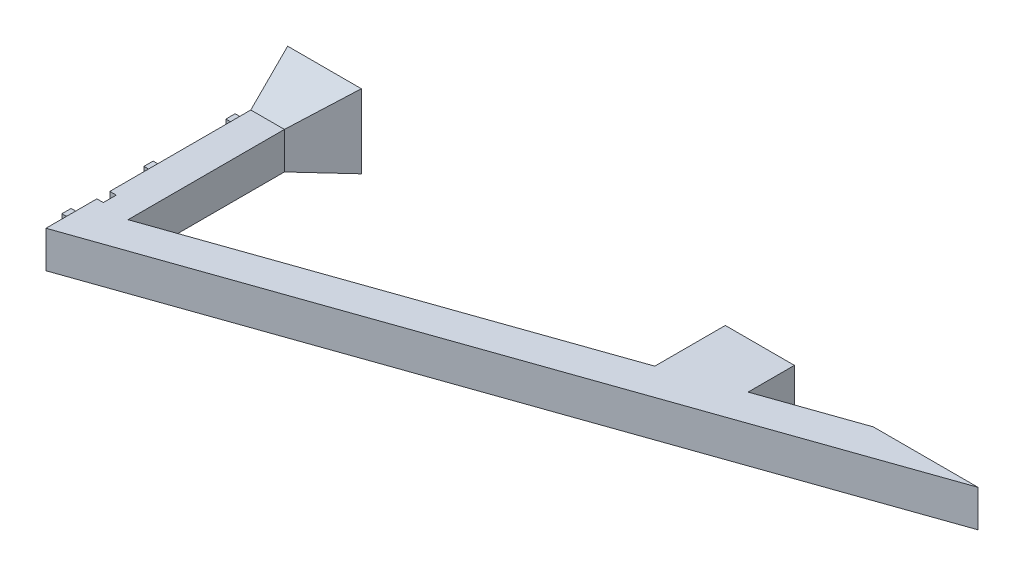
SolidWorks part; units mm, degrees
ref_plane "Přední rovina" through (0, 0, 0) normal (0, 0, 1) x (1, 0, 0)
ref_plane "Horní rovina" through (0, 0, 0) normal (0, 1, 0) x (1, 0, 0)
ref_plane "Pravá rovina" through (0, 0, 0) normal (1, 0, 0) x (0, 0, -1)
sketch "Skica1" plane through (0, 0, 0) normal (0, 1, 0) x (1, 0, 0)
  line L0 (0, 0) -> (0, -55.45)
  line L1 (0, -55.45) -> (149.85, -3)
  line L2 (149.85, -3) -> (127.1478, -3)
  line L3 (127.1478, -3) -> (107, -10.0521)
  line L4 (107, -10.0521) -> (107, 0)
  line L5 (107, 0) -> (92, 0)
  line L6 (92, 0) -> (92, -15.3023)
  line L7 (92, -15.3023) -> (7.3, -44.9487)
  line L8 (7.3, -44.9487) -> (7.3, 0)
  line L9 (7.3, 0) -> (0, 0)
  point P3 (92, -7.6512)
  dimension "D1" = 55.45
  dimension "D2" = 7.3
  dimension "D3" = 15
  dimension "D4" = 3
  dimension "D5" = 7.5
  dimension "D6" = 7.5
  dimension "D7" = 84.7
  dimension "D8" = 149.85
extrude "Přidat vysunutím1" add sketch "Skica1" along normal blind 8
sketch "Skica2" plane through (0, 8, 0) normal (0, 1, 0) x (1, 0, 0)
  line L0 (0, 0) -> (0, -55.45) construction
  line L1 (0, -41.6) -> (1.4, -41.6)
  line L2 (0, -41.6) -> (0, -44.4)
  line L3 (0, -44.4) -> (1.4, -44.4)
  line L4 (1.4, -41.6) -> (1.4, -44.4)
  line L5 (7.3, 0) -> (0, 0) construction
  dimension "D1" = 2.8
  dimension "D2" = 1.4
  dimension "D3" = 41.6
extrude "Odebrat vysunutím1" cut sketch "Skica2" against normal blind 4.4
sketch "Skica3" plane through (0, 0, 0) normal (-1, 0, 0) x (0, 0, 1)
  line L1 (10.4, 5) -> (12.4, 5)
  line L2 (10.4, 5) -> (10.4, 3)
  line L3 (10.4, 3) -> (12.4, 3)
  line L4 (12.4, 5) -> (12.4, 3)
  line L5 (28.2, 5) -> (30.2, 5)
  line L6 (28.2, 5) -> (28.2, 3)
  line L7 (28.2, 3) -> (30.2, 3)
  line L8 (30.2, 5) -> (30.2, 3)
  line L9 (46, 5) -> (48, 5)
  line L10 (46, 5) -> (46, 3)
  line L11 (46, 3) -> (48, 3)
  line L12 (48, 5) -> (48, 3)
  line L13 (0, 8) -> (0, 0) construction
  line L14 (0, 8) -> (41.6, 8) construction
  line L15 (44.4, 8) -> (55.45, 8) construction
  dimension "D1" = 2
  dimension "D2" = 2
  dimension "D3" = 2
  dimension "D4" = 2
  dimension "D5" = 2
  dimension "D6" = 2
  dimension "D7" = 10.4
  dimension "D8" = 3
  dimension "D9" = 3
  dimension "D10" = 3
  dimension "D11" = 15.8
  dimension "D12" = 15.8
extrude "Přidat vysunutím2" add sketch "Skica3" along normal blind 4
sketch "Skica5" plane through (0, 8, 0) normal (0, 1, 0) x (1, 0, 0)
  line L0 (0, 0) -> (0, -41.6) construction
  line L5 (0, -3) -> (16, -3)
  line L6 (0, -3) -> (0, -11)
  line L7 (0, -11) -> (16, -11)
  line L8 (16, -3) -> (16, -11)
  line L9 (7.3, 0) -> (0, 0) construction
  dimension "D1" = 8
  dimension "D2" = 3
  dimension "D3" = 16
extrude "Přidat vysunutím4" add sketch "Skica5" against normal blind 16 from offset 8
sketch "Skica6" plane through (0, 0, 0) normal (-1, 0, 0) x (0, 0, 1)
  line L3 (3, 16) -> (11, 16)
  line L4 (11, 16) -> (11, 8)
  line L5 (11, 8) -> (3, 16)
extrude "Odebrat vysunutím2" cut sketch "Skica6" against normal through all
sketch "Skica7" plane through (0, 0, 0) normal (0, -1, 0) x (1, 0, 0)
  line L3 (7.3, 11) -> (16, 11)
  line L4 (16, 11) -> (16, 3)
  line L5 (16, 3) -> (7.3, 11)
extrude "Odebrat vysunutím3" cut sketch "Skica7" against normal through all
